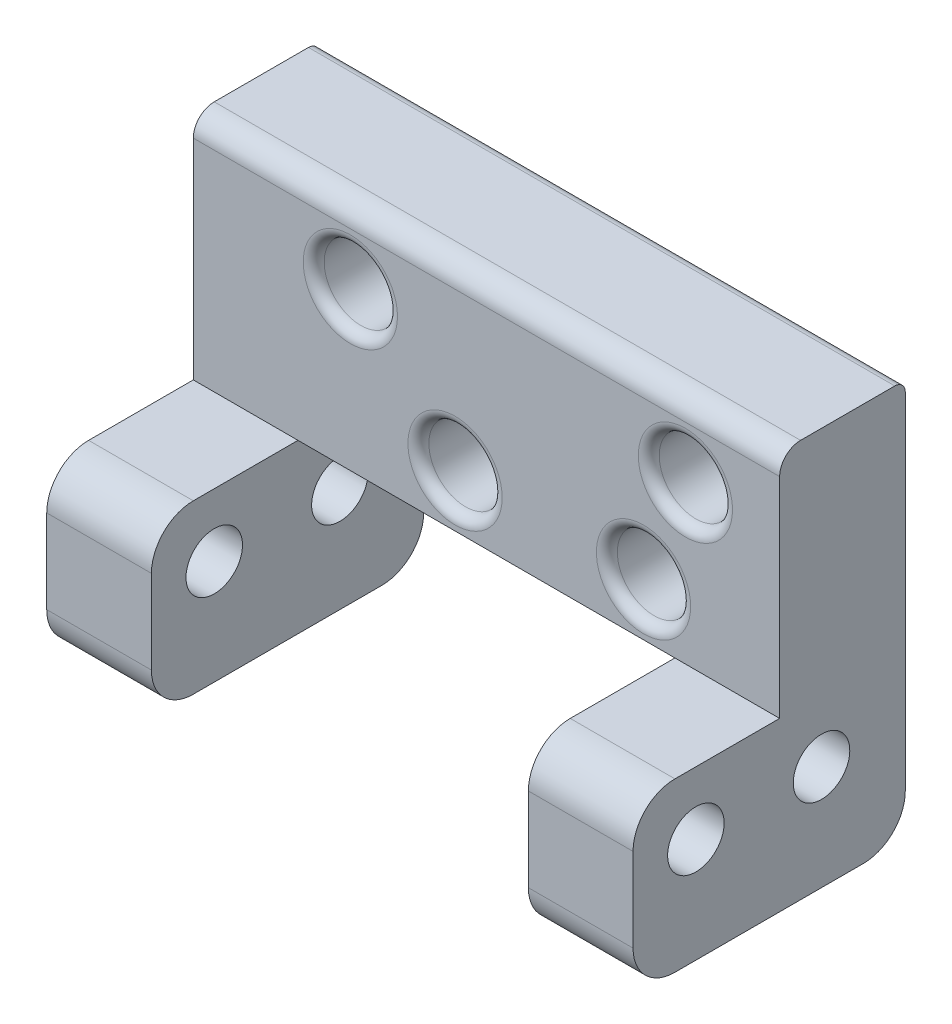
SolidWorks part; units mm, degrees
material "ABS"
ref_plane "前视基准面" through (0, 0, 0) normal (0, 0, 1) x (1, 0, 0)
ref_plane "上视基准面" through (0, 0, 0) normal (0, 1, 0) x (1, 0, 0)
ref_plane "右视基准面" through (0, 0, 0) normal (1, 0, 0) x (0, 0, -1)
sketch "草图1" plane through (0, 0, 0) normal (0, 0, 1) x (1, 0, 0)
  line L0 (0, 0) -> (0, 9.0902) construction
  line L1 (14, 11) -> (-14, 11)
  line L2 (-14, 11) -> (-14, -8)
  line L3 (-14, -8) -> (-9, -8)
  line L4 (-9, 0) -> (-9, -8)
  line L5 (-9, 0) -> (9, 0)
  line L6 (9, 0) -> (9, -8)
  line L7 (14, -8) -> (9, -8)
  line L8 (14, 11) -> (14, -8)
  point P12 (0, 11)
  dimension "D1" = 19
  dimension "D2" = 28
  dimension "D3" = 5
  dimension "D4" = 8
extrude "凸台-拉伸1" add sketch "草图1" along normal blind 6
sketch "草图3" plane through (14, 0, 0) normal (1, 0, 0) x (0, 0, -1)
  line L1 (-6, -8) -> (-13, -8)
  line L2 (-6, -8) -> (-6, 0)
  line L3 (-6, 0) -> (-13, 0)
  line L4 (-13, -8) -> (-13, 0)
  dimension "D1" = 8
  dimension "D2" = 7
extrude "凸台-拉伸2" add sketch "草图3" against normal up to surface (5 mm away) up to face at (9, -4, 3)
sketch "草图2" plane through (14, 0, 0) normal (1, 0, 0) x (0, 0, -1)
  line L0 (-4, 6) -> (-4, -8) construction
  line L1 (-13, -8) -> (0, -8) construction
  line L2 (0, -8) -> (0, 11) construction
  line L4 (0, -8) -> (-13, -8) construction
  line L5 (-10, 2) -> (-10, -8) construction
  circle A0 centre (-4, -3) radius 1.35
  circle A1 centre (-10, -3) radius 1.35
  dimension "D1" = 4
  dimension "D2" = 5
  dimension "D3" = 2.7
  dimension "D4" = 6
extrude "切除-拉伸2" cut sketch "草图2" against normal blind 10
sketch "草图6" plane through (-14, 0, 0) normal (-1, 0, 0) x (0, 0, 1)
  line L0 (6, 0) -> (13, 0) construction
  line L1 (0, -8) -> (13, -8)
  line L2 (0, -8) -> (0, 0)
  line L3 (0, 0) -> (13, 0)
  line L4 (13, -8) -> (13, 0)
  line L5 (13, 0) -> (13, -8) construction
extrude "凸台-拉伸3" add sketch "草图6" against normal up to surface (5 mm away) up to face at (-9, -4, 3)
mirror "镜向4" about plane through (0, 0, 0) normal (1, 0, 0) of "切除-拉伸2"
sketch "草图8" plane through (0, 0, 0) normal (0, 0, -1) x (-1, 0, 0)
  line L0 (14, 11) -> (14, -8) construction
  line L1 (-14, 11) -> (14, 11) construction
  line L2 (-14, -8) -> (-14, 11) construction
  circle A0 centre (-9.5, 7.5) radius 1.75
  circle A1 centre (-7.5, 2.5) radius 1.75
  circle A2 centre (1.5, 2.5) radius 1.75
  circle A3 centre (6.5, 7.5) radius 1.75
  dimension "D1" = 8.5
  dimension "D2" = 3.5
  dimension "D3" = 4.5
  dimension "D4" = 2
  dimension "D5" = 7.5
  dimension "D7" = 3.5
extrude "切除-拉伸3" cut sketch "草图8" against normal blind 10
fillet "圆角1" radius 1 1 edges at (0, 11, 6)
fillet "圆角2" radius 0.5 9 edges at (-4.75, 7.5, 6) (0.25, 2.5, 6) (9.25, 2.5, 6) (11.25, 7.5, 6) (-4.75, 7.5, 0) (0.25, 2.5, 0) (5.75, 2.5, 0) (7.75, 7.5, 0) (0, 11, 0)
fillet "圆角3" radius 2 6 edges at (11.5, -8, 0) (11.5, -8, 13) (11.5, 0, 13) (-11.5, -8, 13) (-11.5, -8, 0) (-11.5, 0, 13)
